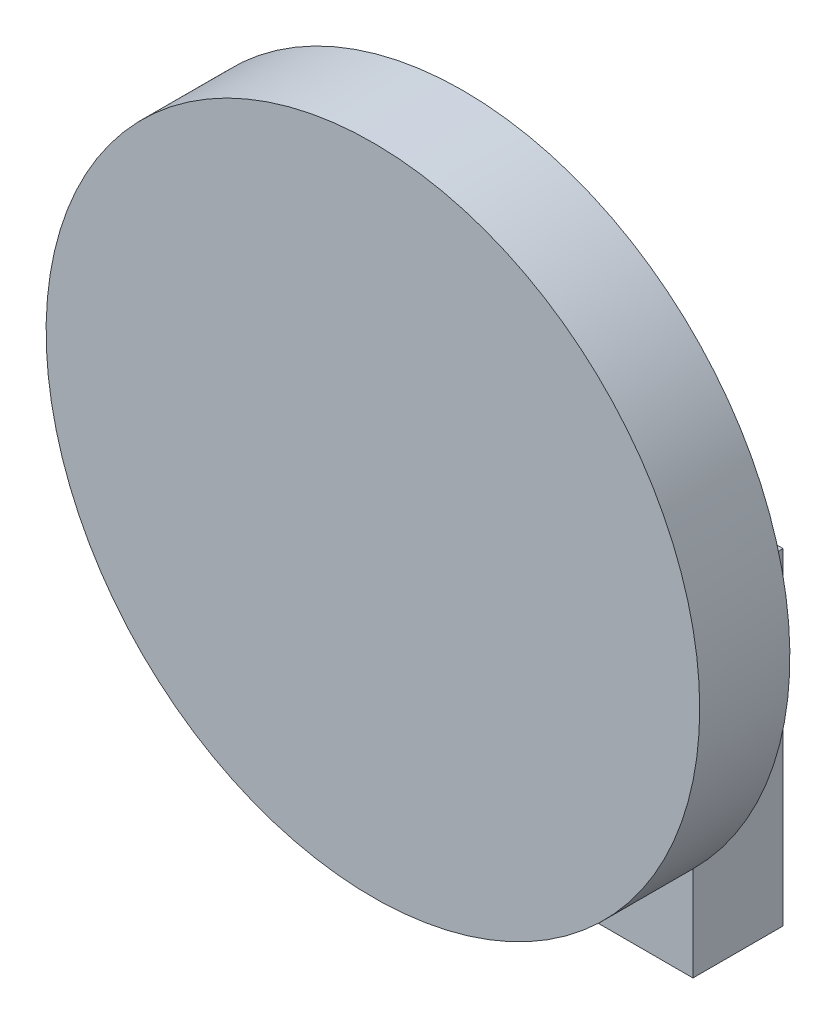
SolidWorks part; units mm, degrees
ref_plane "前视基准面" through (0, 0, 0) normal (0, 0, 1) x (1, 0, 0)
ref_plane "上视基准面" through (0, 0, 0) normal (0, 1, 0) x (1, 0, 0)
ref_plane "右视基准面" through (0, 0, 0) normal (1, 0, 0) x (0, 0, -1)
sketch "草图1" plane through (0, 0, 0) normal (0, 0, 1) x (1, 0, 0)
  line L1 (0, 0) -> (-10.2, 0)
  line L2 (0, 0) -> (0, 7.25)
  line L3 (0, 7.25) -> (-10.2, 7.25)
  line L4 (-10.2, 0) -> (-10.2, 7.25)
  dimension "D1" = 10.2
  dimension "D2" = 7.25
extrude "凸台-拉伸1" add sketch "草图1" along normal blind 2 contours L3 L4 L1 L2
sketch "草图2" plane through (0, 0, 2) normal (0, 0, 1) x (1, 0, 0)
  line L0 (0, 7.25) -> (-10.2, 7.25) construction
  circle A0 centre (-5.1, 7.25) radius 7.25
  dimension "D1" = 14.5
extrude "凸台-拉伸2" add sketch "草图2" along normal blind 2
